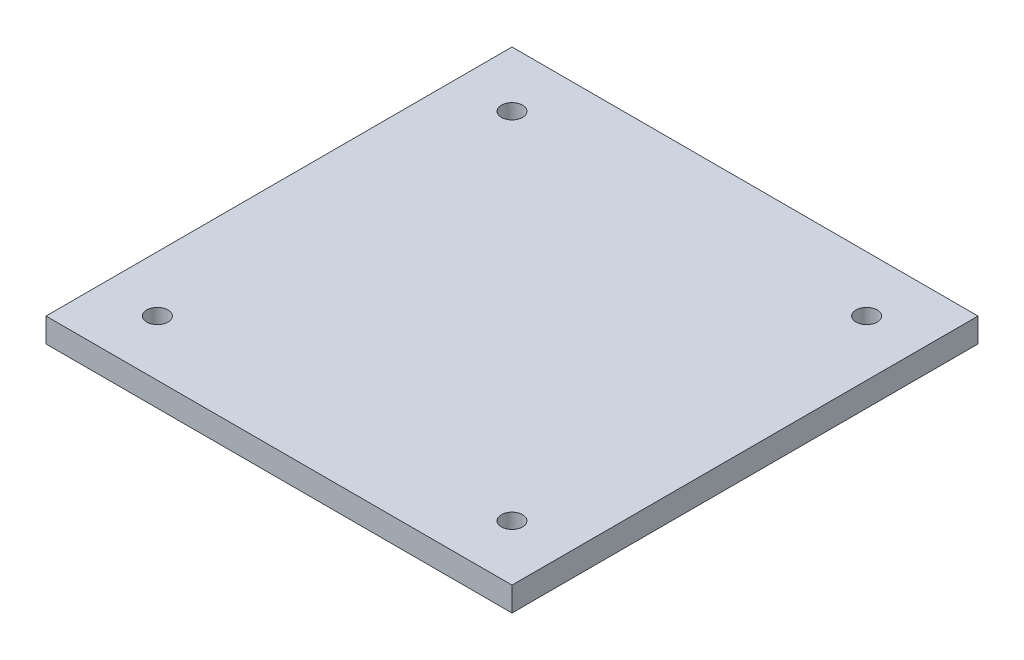
SolidWorks part; units mm, degrees
ref_plane "Front Plane" through (0, 0, 0) normal (0, 0, 1) x (1, 0, 0)
ref_plane "Top Plane" through (0, 0, 0) normal (0, 1, 0) x (1, 0, 0)
ref_plane "Right Plane" through (0, 0, 0) normal (1, 0, 0) x (0, 0, -1)
sketch "Sketch1" plane through (0, 0, 0) normal (0, 1, 0) x (1, 0, 0)
  line L1 (-19.5845, 13.0472) -> (18.9155, 13.0472)
  line L2 (-19.5845, 13.0472) -> (-19.5845, -25.4528)
  line L3 (-19.5845, -25.4528) -> (18.9155, -25.4528)
  line L4 (18.9155, 13.0472) -> (18.9155, -25.4528)
  dimension "D1" = 38.5
  dimension "D2" = 38.5
extrude "Boss-Extrude1" add sketch "Sketch1" along normal blind 2
hole_wizard "M2.2x0.45 Tapped Hole1" positions "3DSketch2" profile "Sketch3" tap size "M2.2x0.45" standard "ANSI Metric" end condition up to next
sketch3d "3DSketch2"
  line L0 (18.9155, 2, -13.0472) -> (-19.5845, 2, -13.0472) construction
  line L1 (-19.5845, 2, -13.0472) -> (-19.5845, 2, 25.4528) construction
  line L2 (-19.5845, 2, 25.4528) -> (18.9155, 2, 25.4528) construction
  line L3 (18.9155, 2, 25.4528) -> (18.9155, 2, -13.0472) construction
  point P0 (-14.9845, 2, -8.4472)
  point P2 (14.3155, 2, 20.8528)
  point P4 (14.3155, 2, -8.4472)
  point P6 (-14.9845, 2, 20.8528)
  dimension "D1" = 4.6
  dimension "D2" = 4.6
  dimension "D3" = 4.6
  dimension "D4" = 4.6
  dimension "D5" = 4.6
  dimension "D6" = 4.6
  dimension "D7" = 4.6
  dimension "D8" = 4.6
sketch "Sketch3" plane through (-14.9845, 2, -8.4472) normal (1, 0, 0) x (0, 0, 1)
  line L0 (0, 0) -> (0, 2)
  line L1 (0, 2) -> (0.875, 2)
  line L2 (0.875, 2) -> (0.875, 0)
  line L5 (0.875, 0) -> (0, 0)
  line L11 (0, -6.35) -> (0, 107.95) construction
  dimension "Thread Major Dia." = 1.75
  dimension "Thru Tap Drill Depth" = 2
equation "\"side length\" = 38.5"
equation "\"hole offset\"= 4.6"
equation "\"D1@Sketch1\"=\"side length\""
equation "\"D2@Sketch1\"=\"side length\""
equation "\"D1@3DSketch2\"=\"hole offset\""
equation "\"D2@3DSketch2\"=\"hole offset\""
equation "\"D3@3DSketch2\"=\"hole offset\""
equation "\"D4@3DSketch2\"=\"hole offset\""
equation "\"D5@3DSketch2\"=\"hole offset\""
equation "\"D6@3DSketch2\"=\"hole offset\""
equation "\"D7@3DSketch2\"=\"hole offset\""
equation "\"D8@3DSketch2\"=\"hole offset\""
